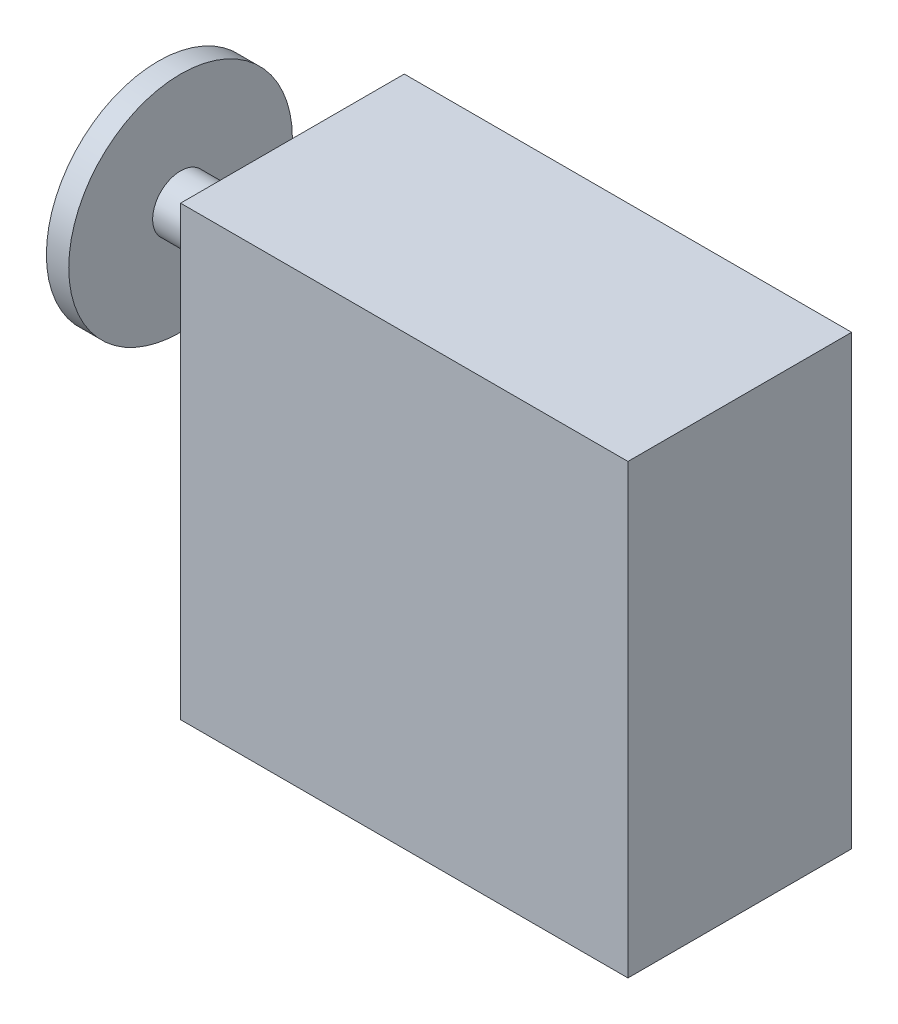
SolidWorks part; units mm, degrees
ref_plane "前视基准面" through (0, 0, 0) normal (0, 0, 1) x (1, 0, 0)
ref_plane "上视基准面" through (0, 0, 0) normal (0, 1, 0) x (1, 0, 0)
ref_plane "右视基准面" through (0, 0, 0) normal (1, 0, 0) x (0, 0, -1)
sketch "草图1" plane through (0, 0, 0) normal (0, 0, 1) x (1, 0, 0)
  line L1 (-20, -20) -> (20, -20)
  line L2 (-20, -20) -> (-20, 20)
  line L3 (-20, 20) -> (20, 20)
  line L4 (20, -20) -> (20, 20)
  line L5 (-20, -20) -> (20, 20) construction
  line L6 (-20, 20) -> (20, -20) construction
  point P0 (0, 0)
  dimension "D1" = 40
  dimension "D2" = 40
extrude "凸台-拉伸1" add sketch "草图1" along normal blind 20
sketch "草图2" plane through (-20, 0, 0) normal (-1, 0, 0) x (0, 0, 1)
  line L0 (0, 20) -> (0, -20) construction
  line L1 (20, 20) -> (0, 20) construction
  circle A0 centre (10, 10) radius 2.5
  dimension "D2" = 10
  dimension "D3" = 5
  dimension "D1" = 10
extrude "凸台-拉伸2" add sketch "草图2" along normal blind 10
sketch "草图3" plane through (-30, 0, 0) normal (-1, 0, 0) x (0, 0, 1)
  circle A0 centre (10, 10) radius 10
  dimension "D1" = 20
extrude "凸台-拉伸3" add sketch "草图3" along normal blind 2
